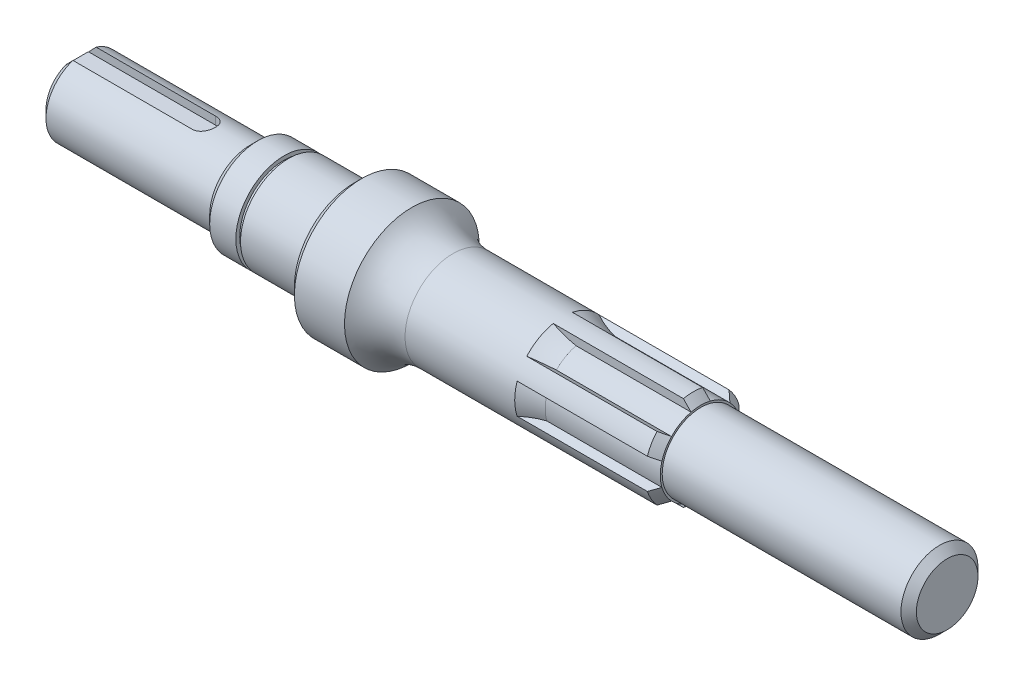
SolidWorks part; units mm, degrees
ref_plane "前视基准面" through (0, 0, 0) normal (0, 0, 1) x (1, 0, 0)
ref_plane "上视基准面" through (0, 0, 0) normal (0, 1, 0) x (1, 0, 0)
ref_plane "右视基准面" through (0, 0, 0) normal (1, 0, 0) x (0, 0, -1)
other "Configuration Table"
sketch "草图1" plane through (0, 0, 0) normal (0, 0, 1) x (1, 0, 0)
  line L0 (0, 0) -> (226, 0) construction
  line L1 (97.7238, -12.5) -> (162, -12.5)
  line L3 (0, -10) -> (0, 10)
  line L4 (0, 10) -> (45, 10)
  line L11 (45, -12.5) -> (45, -10)
  line L12 (45, 12.5) -> (72, 12.5)
  line L15 (72, -17.5) -> (72, -12.5)
  line L16 (72, 17.5) -> (87, 17.5)
  line L20 (97.7238, 12.5) -> (162, 12.5)
  line L21 (162, -12.5) -> (162, -10)
  line L22 (162, 10) -> (162, 12.5)
  line L23 (72, -17.5) -> (87, -17.5)
  line L24 (45, -12.5) -> (72, -12.5)
  line L25 (0, -10) -> (45, -10)
  line L26 (162, -10) -> (226, -10)
  line L29 (162, 10) -> (226, 10)
  line L30 (226, -10) -> (226, 10)
  line L31 (45, 10) -> (45, 12.5)
  line L32 (72, 12.5) -> (72, 17.5)
  arc A0 (97.7238, 12.5) -> (87, 17.5) centre (97.7238, 26.5) cw
  arc A1 (97.7238, -12.5) -> (87, -17.5) centre (97.7238, -26.5) ccw
  point P5 (87, -1.2424)
  point P7 (226, 0)
  point P33 (111.4405, 0)
  dimension "D1" = 14
  dimension "D2" = 20
  dimension "D3" = 25
  dimension "D4" = 35
  dimension "D5" = 25
  dimension "D6" = 45
  dimension "D7" = 72
  dimension "D8" = 87
  dimension "D9" = 20
  dimension "D10" = 226
  dimension "D11" = 64
revolve "旋转1" add sketch "草图1" angle 360 about L0
sketch "草图3" plane through (0, 0, 0) normal (0, 1, 0) x (1, 0, 0)
  line L0 (-33, 0) -> (33, 0) construction
  line L1 (-33, 3) -> (33, 3)
  line L2 (-33, -3) -> (33, -3)
  arc A0 (-33, 3) -> (-33, -3) centre (-33, 0) ccw
  arc A1 (33, -3) -> (33, 3) centre (33, 0) ccw
  point P2 (0, 0)
  dimension "D1" = 3
  dimension "D2" = 33
extrude "切除-拉伸1" cut sketch "草图3" against normal blind 2.5 from offset 10
sketch "草图4" plane through (0, 0, 0) normal (0, 0, 1) x (1, 0, 0)
  line L6 (72, 12.5) -> (45, 12.5) construction
  line L11 (53.8, 12.5) -> (55, 12.5)
  line L12 (53.8, 12.5) -> (53.8, 11.5)
  line L13 (53.8, 11.5) -> (55, 11.5)
  line L14 (55, 12.5) -> (55, 11.5)
  line L15 (0, 0) -> (61.2025, 0) construction
  line L16 (55, -12.5) -> (55, -11.5)
  line L17 (53.8, -11.5) -> (55, -11.5)
  line L18 (53.8, -12.5) -> (53.8, -11.5)
  line L19 (53.8, -12.5) -> (55, -12.5)
  line L20 (45, 12.5) -> (45, -12.5) construction
  dimension "D1" = 8.8
  dimension "D2" = 1.2
  dimension "D3" = 23
revolve "切除-旋转1" cut sketch "草图4" angle 360 about L15
sketch "草图5" plane through (0, 0, 0) normal (0, 0, 1) x (1, 0, 0)
  line L0 (162, 12.5) -> (97.7238, 12.5) construction
  line L1 (162, 12.5) -> (126.2, 12.5)
  line L2 (162, 12.5) -> (162, 10)
  line L3 (162, 10) -> (137.0972, 10)
  line L5 (162, -12.5) -> (162, 12.5) construction
  line L6 (162, 10) -> (226, 10) construction
  line L7 (0, 0) -> (226, 0) construction
  line L8 (0, 0) -> (226, 0) construction
  arc A0 (137.0972, 10) -> (126.2, 12.5) centre (137.0972, 35) cw
  point P5 (162, 8.7042)
  dimension "D1" = 25
  dimension "D2" = 35.8
revolve "切除-旋转2" cut sketch "草图5" angle 360 about L8
sketch "草图8" plane through (226, 0, 0) normal (1, 0, 0) x (0, 0, -1)
  line L0 (0, 0) -> (0, 16.3253) construction
  line L1 (9.3566, 8.2888) -> (7.5818, 7.2641)
  line L3 (-2.5, 12.2474) -> (-2.5, 10.198)
  line L5 (2.5, 12.2474) -> (2.5, 10.198)
  line L6 (11.8566, 3.9587) -> (10.0818, 2.934)
  line L7 (11.8566, -3.9587) -> (10.0818, -2.934)
  line L8 (9.3566, -8.2888) -> (7.5818, -7.2641)
  line L9 (2.5, -12.2474) -> (2.5, -10.198)
  line L10 (-2.5, -12.2474) -> (-2.5, -10.198)
  line L11 (-9.3566, -8.2888) -> (-7.5818, -7.2641)
  line L12 (-11.8566, -3.9587) -> (-10.0818, -2.934)
  line L13 (-11.8566, 3.9587) -> (-10.0818, 2.934)
  line L14 (-9.3566, 8.2888) -> (-7.5818, 7.2641)
  arc A0 (-2.5, 10.198) -> (-7.5818, 7.2641) centre (0, 0) ccw
  arc A1 (-2.5, 12.2474) -> (2.5, 12.2474) centre (0, 0) cw
  circle A2 centre (0, 0) radius 12.5 construction
  arc A3 (9.3566, 8.2888) -> (11.8566, 3.9587) centre (0, 0) cw
  arc A4 (11.8566, -3.9587) -> (9.3566, -8.2888) centre (0, 0) cw
  arc A5 (2.5, -12.2474) -> (-2.5, -12.2474) centre (0, 0) cw
  arc A6 (-9.3566, -8.2888) -> (-11.8566, -3.9587) centre (0, 0) cw
  arc A7 (-11.8566, 3.9587) -> (-9.3566, 8.2888) centre (0, 0) cw
  arc A8 (-10.0818, 2.934) -> (-10.0818, -2.934) centre (0, 0) ccw
  arc A9 (-7.5818, -7.2641) -> (-2.5, -10.198) centre (0, 0) ccw
  arc A10 (2.5, -10.198) -> (7.5818, -7.2641) centre (0, 0) ccw
  arc A11 (10.0818, -2.934) -> (10.0818, 2.934) centre (0, 0) ccw
  arc A12 (7.5818, 7.2641) -> (2.5, 10.198) centre (0, 0) ccw
  dimension "D1" = 21
  dimension "D2" = 5
  dimension "D3" = 6
extrude "凸台-拉伸11" add sketch "草图8" against normal blind 35.8 from offset 64 offset against normal yes
chamfer "倒角1" distance 2 angle 45 10 edges at (226, 0, 10) (162, 6.25, -10.8253) (162, -6.25, -10.8253) (162, -12.5, 0) (162, -6.25, 10.8253) (162, 6.25, 10.8253) (162, 12.5, 0) (72, 0, 17.5) (45, 0, 12.5) (0, -10, 0)
